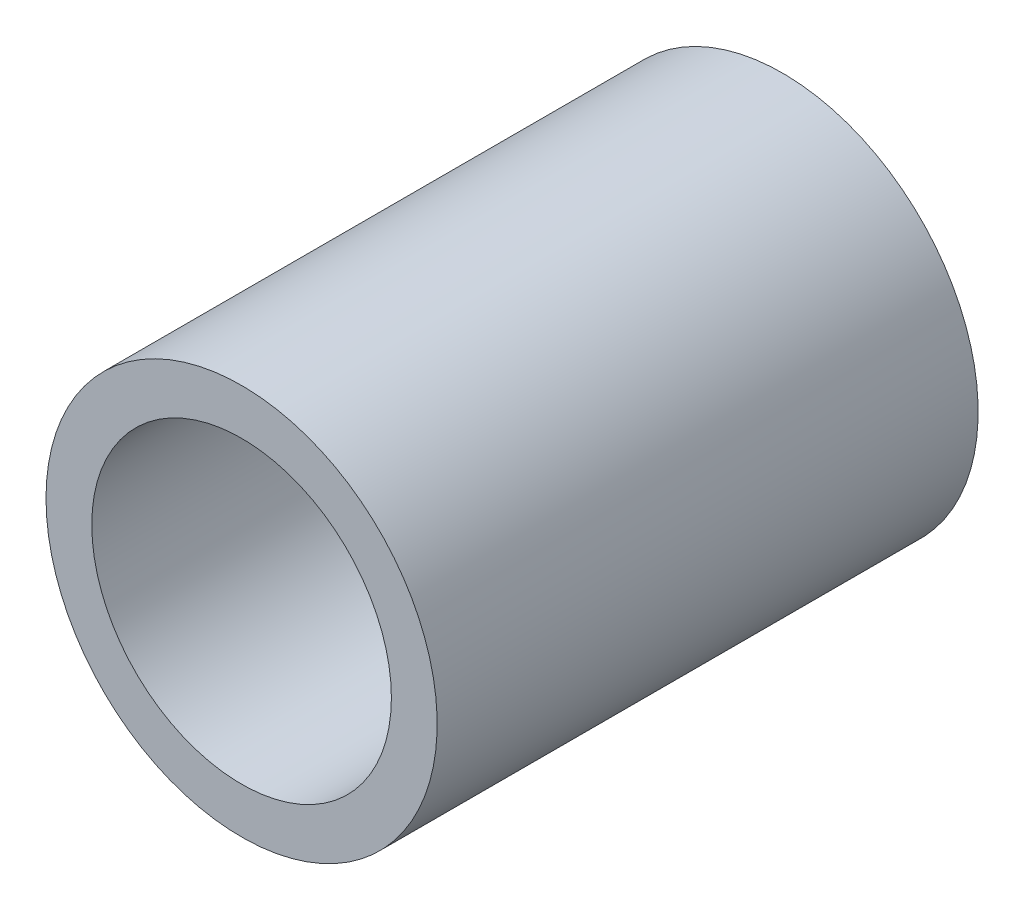
SolidWorks part; units mm, degrees
ref_plane "Plan de face" through (0, 0, 0) normal (0, 0, 1) x (1, 0, 0)
ref_plane "Plan de dessus" through (0, 0, 0) normal (0, 1, 0) x (1, 0, 0)
ref_plane "Plan de droite" through (0, 0, 0) normal (1, 0, 0) x (0, 0, -1)
sketch "Esquisse1" plane through (0, 0, 0) normal (0, 0, 1) x (1, 0, 0)
  circle A0 centre (0, 0) radius 4.7
  circle A1 centre (0, 0) radius 3.6
  dimension "D1" = 9.4
  dimension "D2" = 7.2
extrude "Boss.-Extru.1" add sketch "Esquisse1" along normal blind 13
equation "\"è.2\"=14.4"
